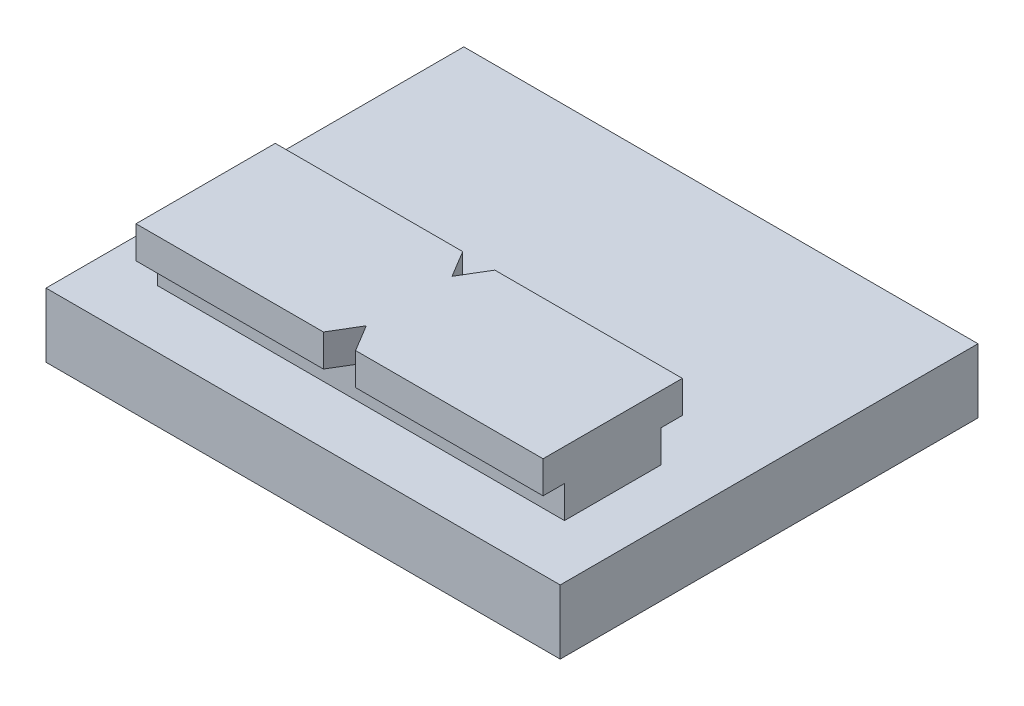
SolidWorks part; units mm, degrees
ref_plane "Front Plane" through (0, 0, 0) normal (0, 0, 1) x (1, 0, 0)
ref_plane "Top Plane" through (0, 0, 0) normal (0, 1, 0) x (1, 0, 0)
ref_plane "Right Plane" through (0, 0, 0) normal (1, 0, 0) x (0, 0, -1)
sketch "Sketch1" plane through (0, 0, 0) normal (0, 1, 0) x (1, 0, 0)
  line L1 (-12, -9.75) -> (12, -9.75)
  line L2 (-12, -9.75) -> (-12, 9.75)
  line L3 (-12, 9.75) -> (12, 9.75)
  line L4 (12, -9.75) -> (12, 9.75)
  line L5 (-12, -9.75) -> (12, 9.75) construction
  line L6 (-12, 9.75) -> (12, -9.75) construction
  point P0 (0, 0)
  dimension "D1" = 19.5
  dimension "D2" = 24
extrude "Boss-Extrude1" add sketch "Sketch1" along normal blind 3
sketch "Sketch3" plane through (0, 3, 0) normal (0, 1, 0) x (1, 0, 0)
  line L0 (-12, -9.75) -> (12, -9.75) construction
  line L1 (-9.5, -7.05) -> (9.5, -7.05)
  line L2 (-9.5, -7.05) -> (-9.5, -2.55)
  line L3 (-9.5, -2.55) -> (9.5, -2.55)
  line L4 (9.5, -7.05) -> (9.5, -2.55)
  line L5 (-9.5, -7.05) -> (9.5, -2.55) construction
  line L6 (-9.5, -2.55) -> (9.5, -7.05) construction
  point P0 (0, -4.8)
  dimension "D1" = 4.5
  dimension "D2" = 2.7
  dimension "D3" = 19
extrude "Boss-Extrude2" add sketch "Sketch3" along normal blind 1.5
sketch "Sketch4" plane through (0, 4.5, 0) normal (0, 1, 0) x (1, 0, 0)
  line L3 (9.5, -7.05) -> (9.5, -2.55) construction
  line L4 (-9.5, -8.05) -> (9.5, -8.05)
  line L5 (-9.5, -8.05) -> (-9.5, -1.55)
  line L6 (-9.5, -1.55) -> (9.5, -1.55)
  line L7 (9.5, -8.05) -> (9.5, -1.55)
  line L8 (-9.5, -8.05) -> (9.5, -1.55) construction
  line L9 (-9.5, -1.55) -> (9.5, -8.05) construction
  line L10 (-9.5, -2.55) -> (-9.5, -7.05) construction
  line L11 (9.5, -2.55) -> (-9.5, -2.55) construction
  line L12 (-9.5, -7.05) -> (9.5, -7.05) construction
  point P4 (0, -4.8)
  dimension "D1" = 1
  dimension "D2" = 1
extrude "Boss-Extrude3" add sketch "Sketch4" along normal blind 1.5
sketch "Sketch5" plane through (0, 6, 0) normal (0, 1, 0) x (1, 0, 0)
  line L0 (0, -2.8) -> (0.75, -1.55)
  line L1 (9.5, -1.55) -> (-9.5, -1.55) construction
  line L2 (0.75, -1.55) -> (-0.75, -1.55)
  line L3 (-0.75, -1.55) -> (0, -2.8)
  line L4 (0, -6.8) -> (0.75, -8.05)
  line L5 (-9.5, -8.05) -> (9.5, -8.05) construction
  line L6 (0.75, -8.05) -> (-0.75, -8.05)
  line L7 (-0.75, -8.05) -> (0, -6.8)
  dimension "D1" = 1.25
  dimension "D2" = 1.25
  dimension "D3" = 1.5
  dimension "D4" = 1.5
  dimension "D5" = 0.75
  dimension "D6" = 0.75
extrude "Cut-Extrude1" cut sketch "Sketch5" against normal up to surface (1.5 mm away) up to face at (-2.375, 4.5, 7.55)
